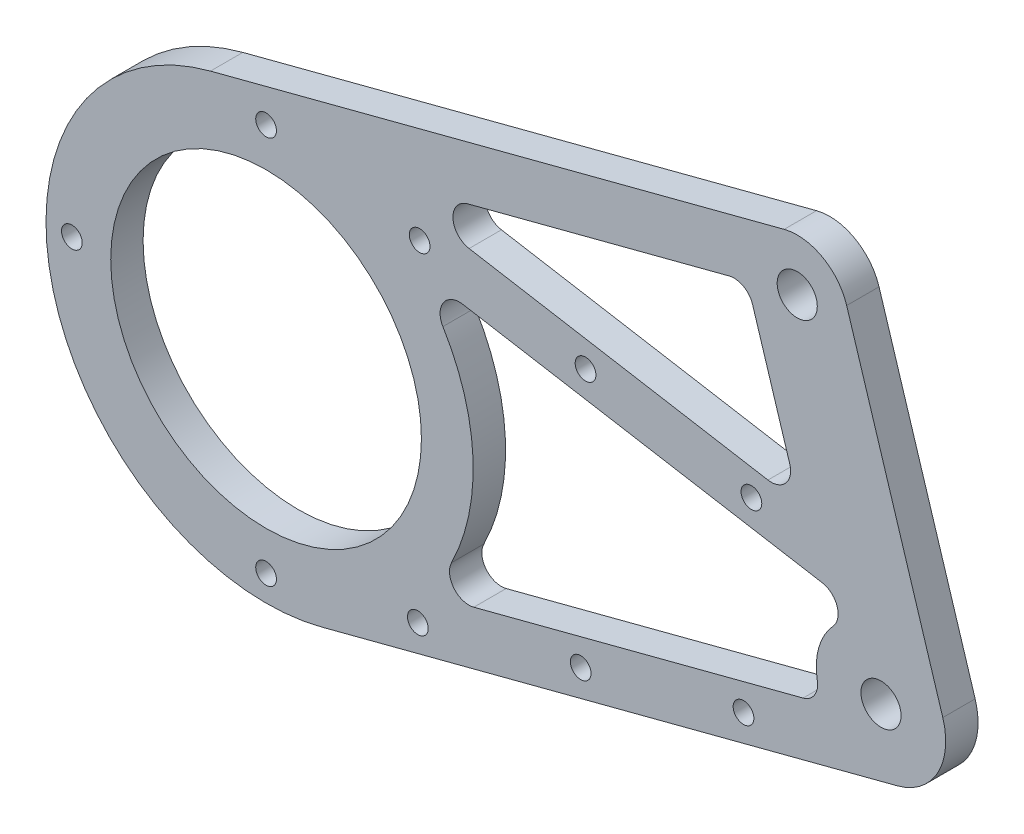
SolidWorks part; units mm, degrees
material "Thornel Mat VMA"
ref_plane "前视基准面" through (0, 0, 0) normal (0, 0, 1) x (1, 0, 0)
ref_plane "上视基准面" through (0, 0, 0) normal (0, 1, 0) x (1, 0, 0)
ref_plane "右视基准面" through (0, 0, 0) normal (1, 0, 0) x (0, 0, -1)
sketch "草图1" plane through (0, 0, 0) normal (0, 0, 1) x (1, 0, 0)
  line L0 (-12.941, 48.2963) -> (0, 0) construction
  line L1 (0, 0) -> (-95, 0) construction
  line L2 (-95, 0) -> (-12.941, 48.2963) construction
  line L3 (-103.5891, 32.8972) -> (-14.9619, 56.0368)
  line L4 (-86.4105, -32.8971) -> (2.5263, -9.6756)
  line L5 (-5.3026, 50.6743) -> (9.548, 2.9725)
  circle A0 centre (0, 0) radius 3.1
  arc A1 (2.5263, -9.6756) -> (9.548, 2.9725) centre (0, 0) ccw
  circle A2 centre (-95, 0) radius 24
  arc A3 (-103.5891, 32.8972) -> (-86.4105, -32.8971) centre (-95, 0) ccw
  circle A4 centre (-12.941, 48.2963) radius 3.1
  arc A5 (-5.3026, 50.6743) -> (-14.9619, 56.0368) centre (-12.941, 48.2963) ccw
  dimension "D3" = 6.2
  dimension "D4" = 6.2
  dimension "D5" = 20
  dimension "D6" = 16
  dimension "D7" = 68
  dimension "D8" = 48
  dimension "D1" = 50
  dimension "D2" = 95
  dimension "D9" = 75
extrude "凸台-拉伸1" add sketch "草图1" along normal blind 5
sketch "草图2" plane through (0, 0, 0) normal (0, 0, -1) x (-1, 0, 0)
  line L0 (71.2744, 26.381) -> (45.6458, 22.002) construction
  line L1 (45.6458, 22.002) -> (20.0172, 17.6231) construction
  line L2 (20.0172, 17.6231) -> (0, 0) construction
  line L3 (0, 0) -> (21.2385, -11.7465) construction
  line L4 (21.2385, -11.7465) -> (46.3951, -18.315) construction
  line L5 (46.3951, -18.315) -> (71.5518, -24.8834) construction
  line L6 (86.4105, -32.8971) -> (-2.5263, -9.6756) construction
  line L7 (95, 0) -> (125, 0) construction
  line L8 (95, 0) -> (95, -30) construction
  circle A9 centre (21.2385, -11.7465) radius 1.6
  circle A10 centre (46.3951, -18.315) radius 1.6
  circle A11 centre (71.5518, -24.8834) radius 1.6
  circle A12 centre (95, -30) radius 1.6
  circle A13 centre (125, 0) radius 1.6
  circle A14 centre (95, 30) radius 1.6
  circle A15 centre (71.2744, 26.381) radius 1.6
  circle A16 centre (45.6458, 22.002) radius 1.6
  circle A17 centre (20.0172, 17.6231) radius 1.6
  circle A18 centre (95, 0) radius 30 construction
  dimension "D1" = 20.0172
  dimension "D9" = 60
  dimension "D10" = 3.2
  dimension "D2" = 17.6231
  dimension "D3" = 26
  dimension "D4" = 26
  dimension "D5" = 21.2385
  dimension "D6" = 11.7465
  dimension "D7" = 26
  dimension "D8" = 25.1566
  dimension "D11" = 24.329
extrude "切除-拉伸1" cut sketch "草图2" against normal blind 44
sketch "草图3" plane through (0, 0, 0) normal (0, 0, -1) x (-1, 0, 0)
  line L0 (71.341, -20.6943) -> (12.0358, -5.2096) construction
  line L1 (9.1138, 11.7021) -> (73.2099, 22.6537) construction
  line L2 (70.3819, -20.4438) -> (8.9749, -4.4104)
  line L3 (-1.6842, 9.8572) -> (72.2328, 22.4867)
  arc A0 (8.9749, -4.4104) -> (-1.6842, 9.8572) centre (0, 0) ccw
  circle A3 centre (95, 0) radius 32
  arc A4 (72.2328, 22.4867) -> (70.3819, -20.4438) centre (95, 0) ccw
  dimension "D1" = 20
  dimension "D2" = 8
extrude "切除-拉伸2" cut sketch "草图3" against normal blind 34
fillet "圆角1" radius 3 4 edges at (1.6842, 9.8572, 2.5) (-72.2328, 22.4867, 2.5) (-70.3819, -20.4438, 2.5) (-8.9749, -4.4104, 2.5)
sketch "草图4" plane through (0, 0, 0) normal (0, 0, -1) x (-1, 0, 0)
  line L2 (12.941, 48.2963) -> (101.5681, 25.1567)
  line L3 (20.6898, 46.2731) -> (77.3564, 31.4781)
  line L5 (63.2687, 29.0711) -> (7.7664, 19.5878)
  line L6 (77.3564, 31.4781) -> (12.6415, 20.4208)
  line L8 (5.7288, -1.7835) -> (20.5794, 45.9183)
  line L9 (12.6415, 20.4208) -> (20.6898, 46.2731)
  dimension "D1" = 8
  dimension "D2" = 8
  dimension "D3" = 16
extrude "切除-拉伸3" cut sketch "草图4" against normal blind 34
fillet "圆角2" radius 3 3 edges at (-77.3564, 31.4781, 2.5) (-20.6898, 46.2731, 2.5) (-12.6415, 20.4208, 2.5)
